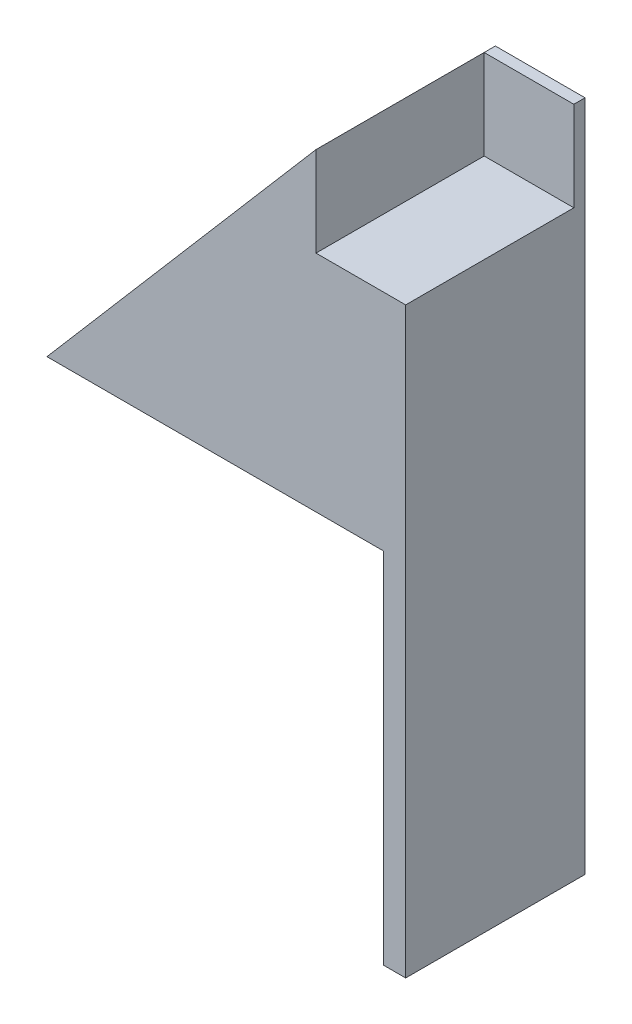
SolidWorks part; units mm, degrees
ref_plane "Front Plane" through (0, 0, 0) normal (0, 0, 1) x (1, 0, 0)
ref_plane "Top Plane" through (0, 0, 0) normal (0, 1, 0) x (1, 0, 0)
ref_plane "Right Plane" through (0, 0, 0) normal (1, 0, 0) x (0, 0, -1)
sketch "Sketch1" plane through (0, 0, 0) normal (0, 0, 1) x (1, 0, 0)
  line L0 (19.05, -50.8) -> (19.05, 0)
  line L1 (9.525, 44.45) -> (-28.575, 0)
  line L2 (9.525, 44.45) -> (22.225, 44.45)
  line L3 (19.05, -50.8) -> (22.225, -50.8)
  line L4 (22.225, 31.75) -> (22.225, -50.8)
  line L5 (22.225, 44.45) -> (22.225, 31.75)
  line L7 (19.05, 0) -> (-28.575, 0)
  point P0 (0, 0)
  dimension "D1" = 3.175
  dimension "D2" = 95.25
  dimension "D3" = 50.8
extrude "Boss-Extrude1" add sketch "Sketch1" along normal mid plane 25.4
sketch "Sketch2" plane through (0, 0, 12.7) normal (0, 0, 1) x (1, 0, 0)
  line L0 (22.225, -50.8) -> (22.225, 44.45) construction
  line L1 (9.525, 44.45) -> (22.225, 44.45)
  line L2 (9.525, 44.45) -> (9.525, 31.75)
  line L3 (9.525, 31.75) -> (22.225, 31.75)
  line L4 (22.225, 44.45) -> (22.225, 31.75)
  dimension "D1" = 12.7
  dimension "D2" = 12.7
extrude "Cut-Extrude1" cut sketch "Sketch2" against normal blind 23.8125
